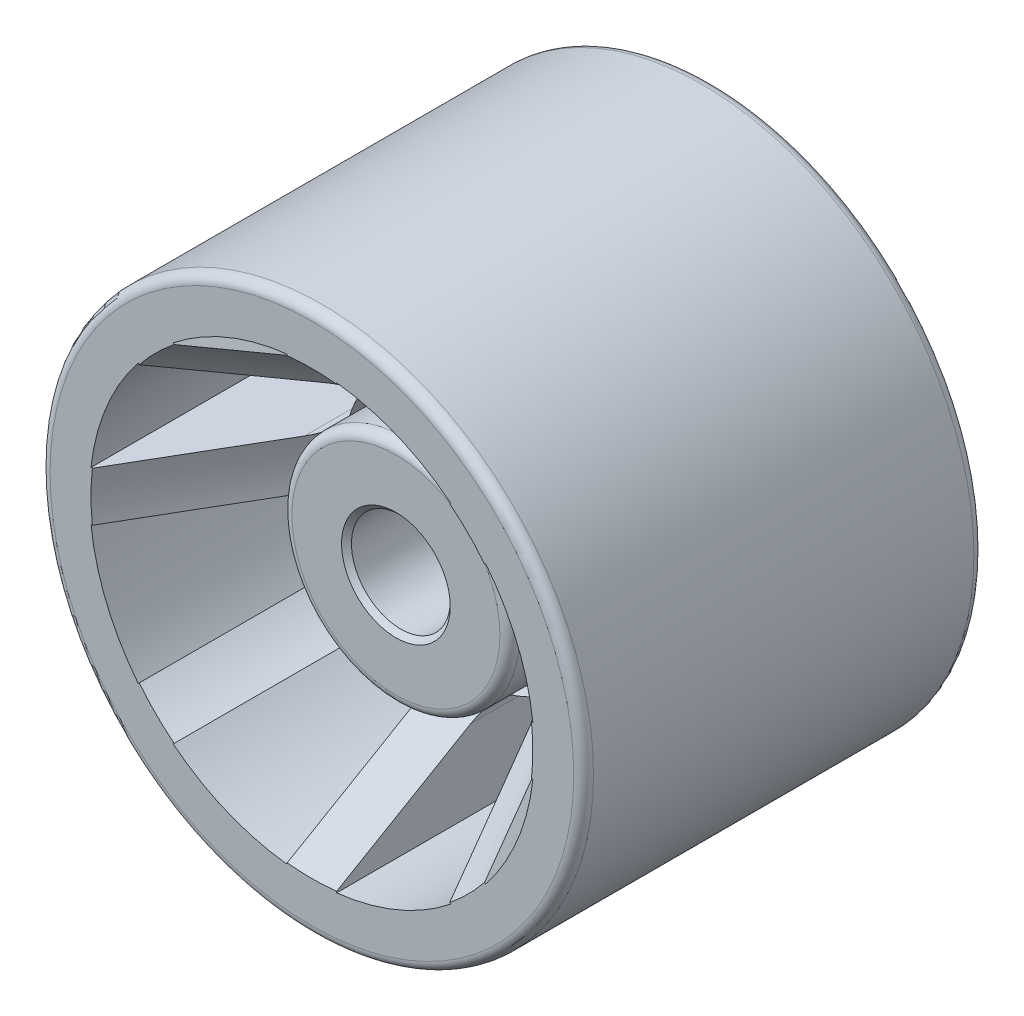
SolidWorks part; units mm, degrees
material "PA Typ 6"
ref_plane "Ebene vorne" through (0, 0, 0) normal (0, 0, 1) x (1, 0, 0)
ref_plane "Ebene oben" through (0, 0, 0) normal (0, 1, 0) x (1, 0, 0)
ref_plane "Ebene rechts" through (0, 0, 0) normal (1, 0, 0) x (0, 0, -1)
sketch "Skizze1" plane through (0, 0, 0) normal (0, 0, 1) x (1, 0, 0)
  circle A0 centre (0, 0) radius 27.5
  dimension "D1" = 55
extrude "Aufsatz-Linear austragen1" add sketch "Skizze1" along normal blind 40.5
sketch "Skizze2" plane through (0, 0, 40.5) normal (0, 0, 1) x (1, 0, 0)
  line L0 (0, 27.5) -> (0, -27.5) construction
  line L1 (-27.5, 0) -> (27.5, 0) construction
  line L2 (-19.4454, -19.4454) -> (19.4454, 19.4454) construction
  line L3 (19.4454, -19.4454) -> (-19.4454, 19.4454) construction
  line L4 (-14.0436, 17.5792) -> (-7.253, 10.7886)
  line L5 (-2.5, 22.3607) -> (-2.5, 12.7574)
  line L6 (14.0436, 17.5792) -> (7.253, 10.7886)
  line L7 (2.5, 22.3607) -> (2.5, 12.7574)
  line L8 (22.3607, 2.5) -> (12.7574, 2.5)
  line L9 (17.5792, 14.0436) -> (10.7886, 7.253)
  line L10 (17.5792, -14.0436) -> (10.7886, -7.253)
  line L11 (22.3607, -2.5) -> (12.7574, -2.5)
  line L12 (2.5, -22.3607) -> (2.5, -12.7574)
  line L13 (14.0436, -17.5792) -> (7.253, -10.7886)
  line L14 (-14.0436, -17.5792) -> (-7.253, -10.7886)
  line L15 (-2.5, -22.3607) -> (-2.5, -12.7574)
  line L16 (-22.3607, -2.5) -> (-12.7574, -2.5)
  line L17 (-17.5792, -14.0436) -> (-10.7886, -7.253)
  line L18 (-17.5792, 14.0436) -> (-10.7886, 7.253)
  line L19 (-22.3607, 2.5) -> (-12.7574, 2.5)
  circle A0 centre (0, 0) radius 27.5 construction
  circle A1 centre (0, 0) radius 5
  circle A2 centre (0, 0) radius 13 construction
  circle A3 centre (0, 0) radius 22.5 construction
  arc A4 (-14.0436, 17.5792) -> (-2.5, 22.3607) centre (0, 0) cw
  arc A5 (-7.253, 10.7886) -> (-2.5, 12.7574) centre (0, 0) cw
  arc A6 (2.5, 12.7574) -> (7.253, 10.7886) centre (0, 0) cw
  arc A7 (2.5, 22.3607) -> (14.0436, 17.5792) centre (0, 0) cw
  arc A8 (10.7886, 7.253) -> (12.7574, 2.5) centre (0, 0) cw
  arc A9 (17.5792, 14.0436) -> (22.3607, 2.5) centre (0, 0) cw
  arc A10 (12.7574, -2.5) -> (10.7886, -7.253) centre (0, 0) cw
  arc A11 (22.3607, -2.5) -> (17.5792, -14.0436) centre (0, 0) cw
  arc A12 (7.253, -10.7886) -> (2.5, -12.7574) centre (0, 0) cw
  arc A13 (14.0436, -17.5792) -> (2.5, -22.3607) centre (0, 0) cw
  arc A14 (-2.5, -12.7574) -> (-7.253, -10.7886) centre (0, 0) cw
  arc A15 (-2.5, -22.3607) -> (-14.0436, -17.5792) centre (0, 0) cw
  arc A16 (-10.7886, -7.253) -> (-12.7574, -2.5) centre (0, 0) cw
  arc A17 (-17.5792, -14.0436) -> (-22.3607, -2.5) centre (0, 0) cw
  arc A18 (-12.7574, 2.5) -> (-10.7886, 7.253) centre (0, 0) cw
  arc A19 (-22.3607, 2.5) -> (-17.5792, 14.0436) centre (0, 0) cw
  point P53 (0, 0)
  dimension "D3" = 10
  dimension "D4" = 8
  dimension "D5" = 5
  dimension "D1" = 45
  dimension "D2" = 45
  dimension "D6" = 5
  dimension "D7" = 5
  dimension "D8" = 8
extrude "Schnitt-Linear austragen1" cut sketch "Skizze2" against normal through all
fillet "Verrundung1" radius 2 16 edges at (2.5, -12.7574, 20.25) (7.253, -10.7886, 20.25) (-7.253, -10.7886, 20.25) (-2.5, -12.7574, 20.25) (-12.7574, -2.5, 20.25) (-10.7886, -7.253, 20.25) (-10.7886, 7.253, 20.25) (-12.7574, 2.5, 20.25) (7.253, 10.7886, 20.25) (2.5, 12.7574, 20.25) (12.7574, 2.5, 20.25) (10.7886, 7.253, 20.25) (10.7886, -7.253, 20.25) (12.7574, -2.5, 20.25) (-2.5, 12.7574, 20.25) (-7.253, 10.7886, 20.25)
ref_axis "Achse1" through (0, 0, 0) along (0, 0, 1)
ref_plane "Ebene1" through (0, 0, 20.25) normal (0, 0, 1) x (1, 0, 0)
sketch "Skizze3" plane through (0, 0, 0) normal (0, 1, 0) x (1, 0, 0)
  line L0 (11.5267, -21.735) -> (11.5267, -40.5)
  line L2 (11.5267, -40.5) -> (22.3607, -40.5)
  line L3 (-30.25, -20.25) -> (30.25, -20.25) construction
  line L4 (11.5267, 0) -> (22.3607, 0)
  line L5 (11.5267, -18.765) -> (11.5267, 0)
  line L6 (11.5267, 0) -> (11.5267, -40.5) construction
  line L7 (22.3607, -40.5) -> (11.5267, -21.735)
  line L8 (11.5267, -18.765) -> (22.3607, 0)
  line L9 (14.3091, -40.5) -> (22.3607, -40.5) construction
  line L10 (22.3607, 0) -> (22.3607, -40.5) construction
  line L11 (12.4012, 0) -> (11.5267, 0) construction
  dimension "D1" = 60
revolve "Schnitt-Rotation1" cut sketch "Skizze3" angle 360 about axis through (0, 0, 0) along (0, 0, 1)
sketch "Skizze4" plane through (0, 0, 40.5) normal (0, 0, 1) x (1, 0, 0)
  circle A0 centre (0, 0) radius 11.5267
  circle A1 centre (0, 0) radius 11.5267 construction
extrude "Schnitt-Linear austragen2" cut sketch "Skizze4" against normal blind 8.5
sketch "Skizze5" plane through (0, 0, 0) normal (0, 0, -1) x (-1, 0, 0)
  circle A0 centre (0, 0) radius 11.5267
  circle A1 centre (0, 0) radius 11.5267 construction
extrude "Schnitt-Linear austragen3" cut sketch "Skizze5" against normal blind 8.5
sketch "Skizze6" plane through (0, 0, 32) normal (0, 0, 1) x (1, 0, 0)
  circle A0 centre (0, 0) radius 5
  dimension "D1" = 10
extrude "Schnitt-Linear austragen4" [suppressed] cut sketch "Skizze6" against normal blind 7
fillet "Verrundung3" [suppressed] radius 5
fillet "Verrundung4" [suppressed] radius 1
fillet "Verrundung5" radius 1 2 edges at (27.5, 0, 0) (27.5, 0, 40.5)
fillet "Verrundung6" [suppressed] radius 1
fillet "Verrundung7" [suppressed] radius 1
fillet "Verrundung8" radius 1 2 edges at (11.5267, 0, 32) (-11.5267, 0, 8.5)
sketch "Skizze7" plane through (0, 0, 8.5) normal (0, 0, -1) x (-1, 0, 0)
  circle A0 centre (0, 0) radius 4.8
  dimension "D1" = 9.6
extrude "Schnitt-Linear austragen5" [suppressed] cut sketch "Skizze7" against normal blind 7
chamfer "Fase1" distance 0.5 angle 45 2 edges at (-5, 0, 8.5) (5, 0, 32)
